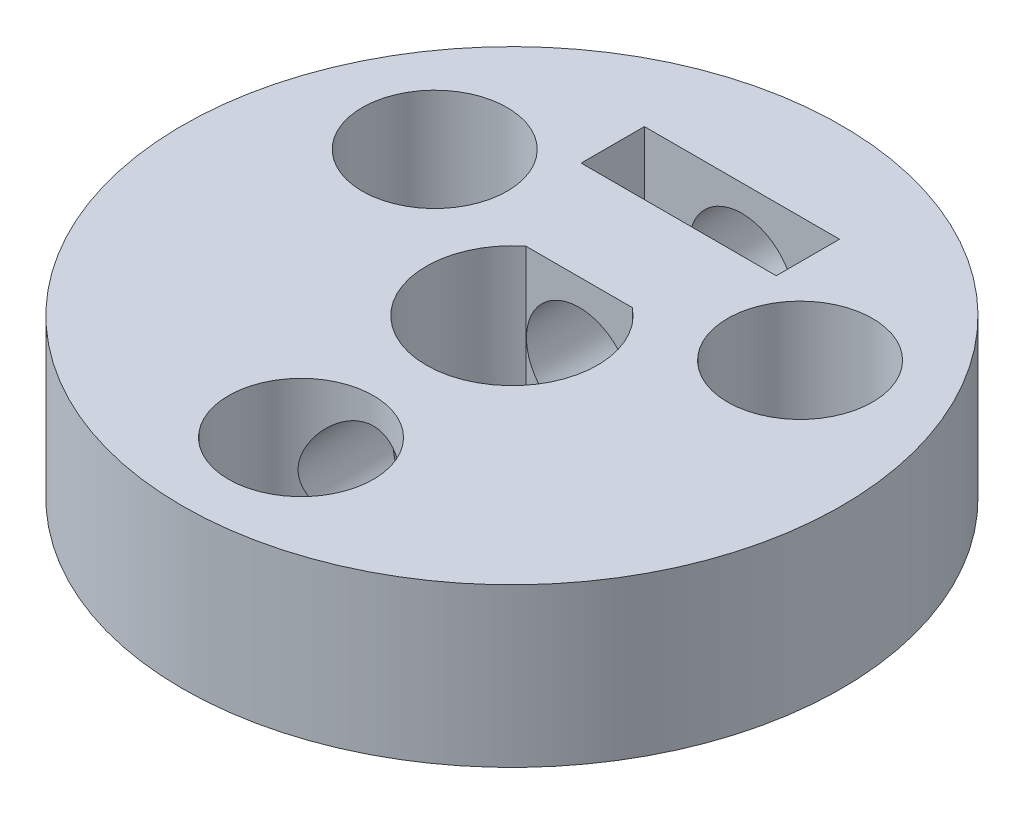
SolidWorks part; units mm, degrees
ref_plane "Front Plane" through (0, 0, 0) normal (0, 0, 1) x (1, 0, 0)
ref_plane "Top Plane" through (0, 0, 0) normal (0, 1, 0) x (1, 0, 0)
ref_plane "Right Plane" through (0, 0, 0) normal (1, 0, 0) x (0, 0, -1)
sketch "Sketch1" plane through (0, 0, 0) normal (0, 1, 0) x (1, 0, 0)
  circle A0 centre (0, 0) radius 12.5
  dimension "D1" = 25
extrude "Boss-Extrude1" add sketch "Sketch1" along normal blind 6
sketch "Sketch2" plane through (0, 6, 0) normal (0, 1, 0) x (1, 0, 0)
  line L0 (-2.0149, 2.55) -> (2.0149, 2.55) construction
  line L1 (0, -3.25) -> (0, 0) construction
  line L2 (-2.0149, 2.55) -> (2.0149, 2.55)
  circle A0 centre (0, 0) radius 3.25
  dimension "D1" = 6.5
  dimension "D2" = 5.8
extrude "Cut-Extrude1" cut sketch "Sketch2" against normal up to next contours L2 A0
sketch "Sketch3" plane through (0, 6, 0) normal (0, 1, 0) x (1, 0, 0)
  line L0 (0, 0) -> (0, -12.5) construction
  circle A0 centre (0, 0) radius 12.5 construction
  circle A1 centre (0, -8) radius 2.75
  circle A2 centre (-6.9282, 4) radius 2.75
  circle A3 centre (6.9282, 4) radius 2.75
  point P15 (0, 0)
  dimension "D1" = 5.5
  dimension "D2" = 8
  dimension "D4" = 6.9282
  dimension "D5" = 4
  dimension "D3" = 3
extrude "Cut-Extrude2" cut sketch "Sketch3" against normal up to next
sketch "Sketch4" plane through (0, 0, -2.55) normal (0, 0, 1) x (1, 0, 0)
  line L0 (0, 0) -> (0, 6) construction
  line L1 (2.0149, 0) -> (-2.0149, 0) construction
  line L2 (-2.0149, 6) -> (2.0149, 6) construction
  circle A0 centre (0, 3) radius 2
  dimension "D1" = 4
extrude "Cut-Extrude3" cut sketch "Sketch4" against normal up to next and the other way up to next
sketch "Sketch5" plane through (0, 6, 0) normal (0, 1, 0) x (1, 0, 0)
  line L0 (0, 2.55) -> (0, 12.5) construction
  line L1 (-2.0149, 2.55) -> (2.0149, 2.55) construction
  line L3 (-3.7, 6.325) -> (3.7, 6.325)
  line L4 (-3.7, 6.325) -> (-3.7, 8.725)
  line L5 (-3.7, 8.725) -> (3.7, 8.725)
  line L6 (3.7, 6.325) -> (3.7, 8.725)
  line L7 (-3.7, 6.325) -> (3.7, 8.725) construction
  line L8 (-3.7, 8.725) -> (3.7, 6.325) construction
  circle A0 centre (0, 0) radius 12.5 construction
  point P7 (0, 7.525)
  dimension "D1" = 7.4
  dimension "D2" = 2.4
extrude "Cut-Extrude4" cut sketch "Sketch5" against normal up to next
